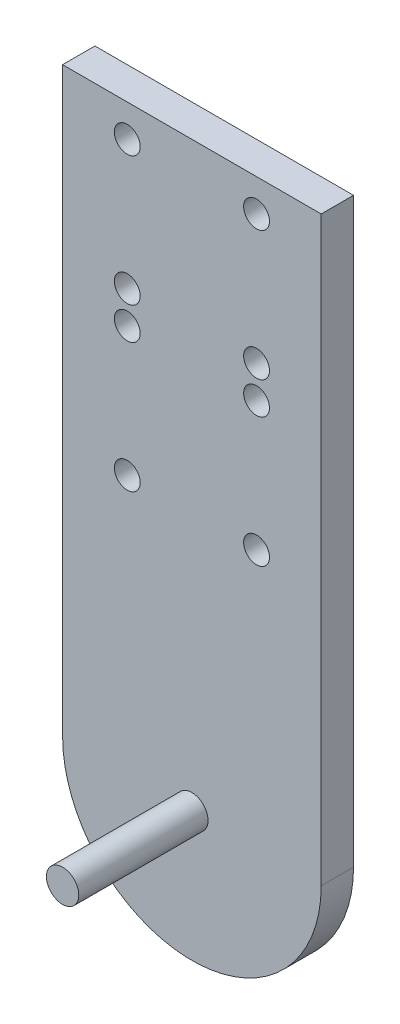
SolidWorks part; units mm, degrees
ref_plane "Front Plane" through (0, 0, 0) normal (0, 0, 1) x (1, 0, 0)
ref_plane "Top Plane" through (0, 0, 0) normal (0, 1, 0) x (1, 0, 0)
ref_plane "Right Plane" through (0, 0, 0) normal (1, 0, 0) x (0, 0, -1)
sketch "Sketch1" plane through (0, 0, 0) normal (0, 0, 1) x (1, 0, 0)
  line L0 (-40, 90) -> (0, 90)
  line L2 (0, 0) -> (0, 90)
  line L4 (-40, 0) -> (-40, 90)
  arc A0 (-40, 0) -> (0, 0) centre (-20, 0) ccw
  dimension "D1" = 40
  dimension "D2" = 90
extrude "Boss-Extrude1" add sketch "Sketch1" along normal blind 5
sketch "Sketch2" plane through (0, 0, 5) normal (0, 0, 1) x (1, 0, 0)
  circle A0 centre (-20, 0) radius 2.5
  dimension "D1" = 5
extrude "Boss-Extrude2" add sketch "Sketch2" along normal blind 20
sketch "Sketch3" plane through (0, 0, 5) normal (0, 0, 1) x (1, 0, 0)
  line L0 (-20, 90) -> (-10, 90)
  line L1 (0, 90) -> (-40, 90) construction
  line L2 (-20, 90) -> (-30, 90)
  line L3 (-30, 90) -> (-30, 85)
  line L4 (-10, 90) -> (-10, 85)
  circle A0 centre (-30, 85) radius 2
  circle A1 centre (-10, 85) radius 2
  dimension "D5" = 4
  dimension "D6" = 4
  dimension "D1" = 10
  dimension "D2" = 10
  dimension "D3" = 5
  dimension "D4" = 5
extrude "Cut-Extrude1" cut sketch "Sketch3" against normal blind 50
sketch "Sketch5" plane through (0, 0, 5) normal (0, 0, 1) x (1, 0, 0)
  line L0 (-20, 90) -> (-30, 90)
  line L1 (0, 90) -> (-40, 90) construction
  line L2 (-20, 90) -> (-10, 90)
  line L3 (-30, 90) -> (-30, 60)
  line L4 (-10, 90) -> (-10, 60)
  circle A0 centre (-30, 60) radius 2
  circle A1 centre (-10, 60) radius 2
  dimension "D5" = 4
  dimension "D6" = 4
  dimension "D1" = 10
  dimension "D2" = 10
  dimension "D3" = 30
  dimension "D4" = 30
extrude "Cut-Extrude2" cut sketch "Sketch5" against normal blind 50
pattern_linear "LPattern1" count 2 spacing 20 along (0, -1, 0) of "Cut-Extrude1", "Cut-Extrude2"
